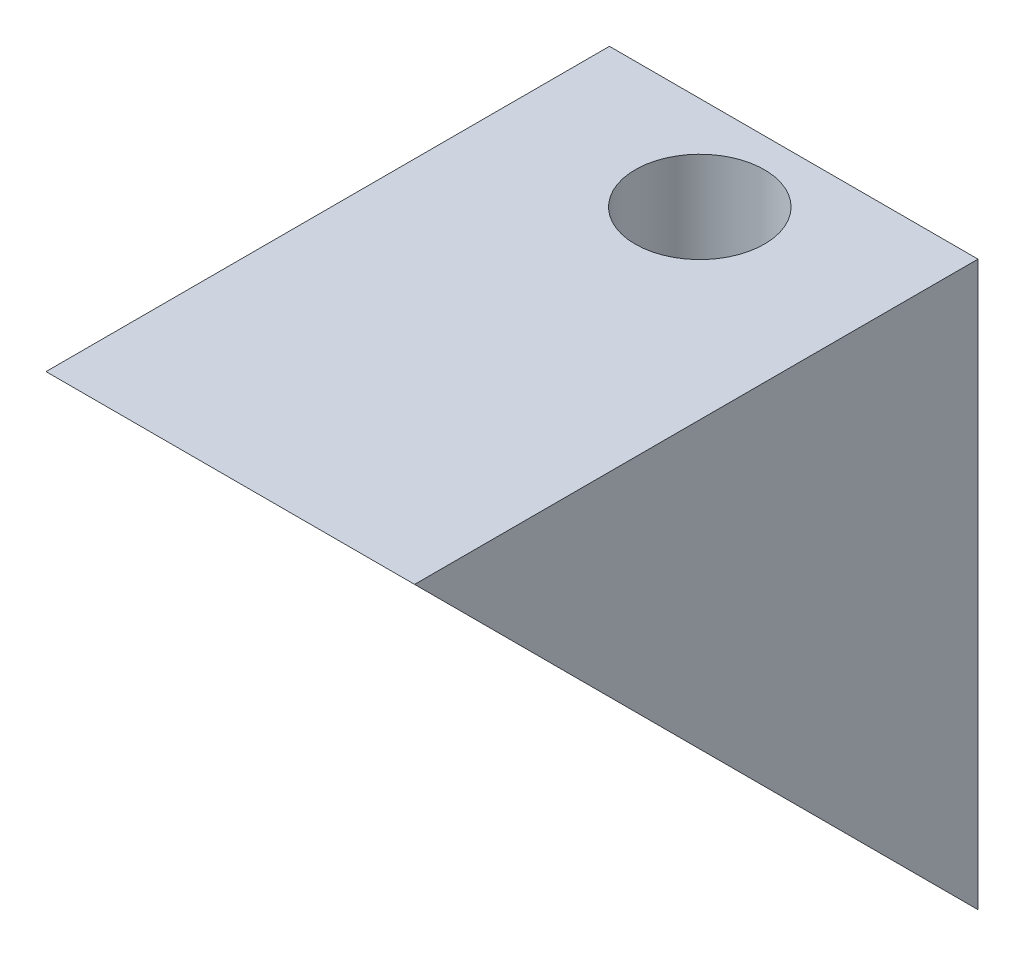
SolidWorks part; units mm, degrees
ref_plane "Front Plane" through (0, 0, 0) normal (0, 0, 1) x (1, 0, 0)
ref_plane "Top Plane" through (0, 0, 0) normal (0, 1, 0) x (1, 0, 0)
ref_plane "Right Plane" through (0, 0, 0) normal (1, 0, 0) x (0, 0, -1)
sketch "Sketch1" plane through (0, 0, 0) normal (1, 0, 0) x (0, 0, -1)
  line L0 (0, 209.1214) -> (0, -209.1214) construction
  line L1 (97.4048, 0) -> (-97.4048, 0) construction
  line L2 (29.1314, 92.5) -> (-29.1314, 92.5) construction
  line L3 (282.5499, -150) -> (-282.5499, -150) construction
  line L4 (24.4822, 10) -> (-24.4822, 10) construction
  line L5 (-12.5, 92.5) -> (-12.5, 10) construction
  line L6 (12.5, 10) -> (12.5, 92.5) construction
  line L7 (97.4048, -90) -> (-97.4048, -90) construction
  point P4 (0, 0)
  point P8 (0, 0)
  point P11 (0, 92.5)
  point P14 (0, -150)
  point P17 (0, 10)
  point P24 (0, -90)
  dimension "D1" = 92.5
  dimension "D2" = 150
  dimension "D3" = 10
  dimension "D4" = 25
  dimension "D5" = 12.5
  dimension "D6" = 100
sketch "Sketch2" plane through (0, 0, 0) normal (1, 0, 0) x (0, 0, -1)
  line L0 (-100, -24.356) -> (20, -144.356)
  line L1 (-100, -24.356) -> (20, -24.356)
  line L2 (20, -24.356) -> (20, -144.356)
  line L3 (0, 209.1214) -> (0, -209.1214) construction
  line L4 (29.1314, 92.5) -> (-29.1314, 92.5) construction
  dimension "D1" = 45
  dimension "D2" = 120
  dimension "D3" = 20
  dimension "D4" = 116.856
extrude "Boss-Extrude1" add sketch "Sketch2" along normal mid plane 78.5
sketch "Sketch4" plane through (0, -24.356, 0) normal (0, 1, 0) x (1, 0, 0)
  line L0 (0, 282.5499) -> (0, -282.5499) construction
  circle A0 centre (0, 0) radius 13.75
  dimension "D1" = 27.5
extrude "Cut-Extrude1" cut sketch "Sketch4" against normal blind 30
sketch "Sketch5" plane through (0, 0, -20) normal (0, 0, -1) x (-1, 0, 0)
  line L0 (0, 0) -> (0, -125.6856) construction
  line L1 (-39.25, -24.356) -> (39.25, -24.356) construction
  circle A0 centre (0, -59.356) radius 3.5
  circle A1 centre (0, -74.356) radius 3.5
  dimension "D1" = 7
  dimension "D2" = 7
  dimension "D3" = 35
  dimension "D4" = 15
sketch "Sketch6" plane through (0, -54.356, 0) normal (0, 1, 0) x (1, 0, 0)
  circle A0 centre (0, 0) radius 10.2
  dimension "D1" = 20.4
ref_plane "Plane1" through (0, -84.356, 0) normal (0, 1, 0) x (1, 0, 0)
sketch "Sketch7" plane through (0, -84.356, 0) normal (0, 1, 0) x (1, 0, 0)
  circle A0 centre (0, 0) radius 9.75
  dimension "D1" = 19.5
loft "Cut-Loft1" cut profiles "Sketch7", "Sketch6"
extrude "Cut-Extrude2" cut sketch "Sketch5" against normal blind 15
